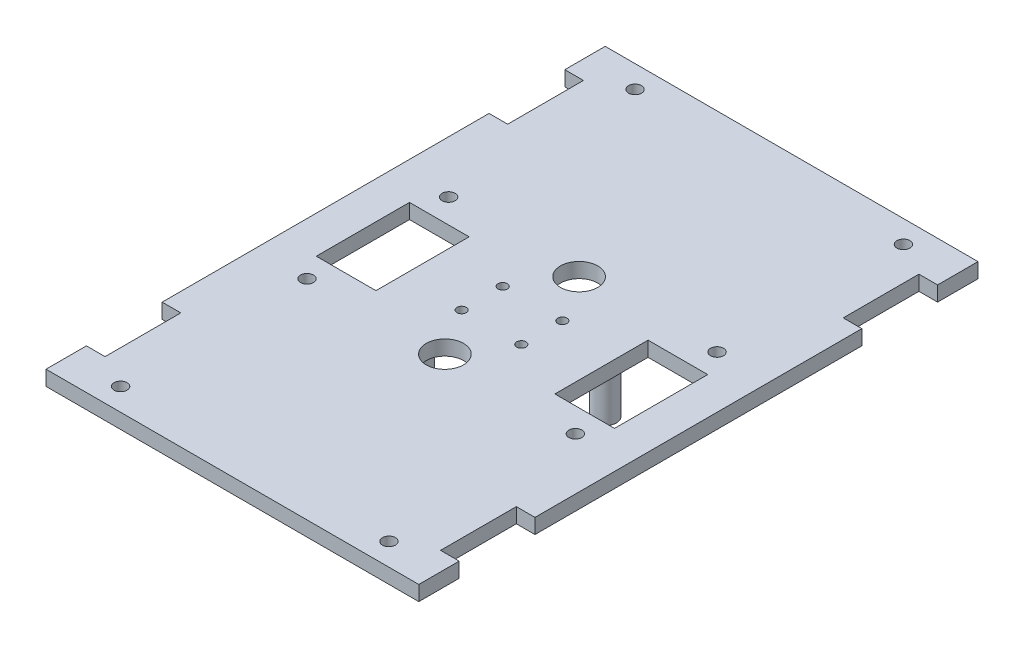
SolidWorks part; units mm, degrees
ref_plane "前视基准面" through (0, 0, 0) normal (0, 0, 1) x (1, 0, 0)
ref_plane "上视基准面" through (0, 0, 0) normal (0, 1, 0) x (1, 0, 0)
ref_plane "右视基准面" through (0, 0, 0) normal (1, 0, 0) x (0, 0, -1)
sketch "草图1" plane through (0, 0, 0) normal (0, 1, 0) x (1, 0, 0)
  line L0 (0, 0) -> (0, 8.8316) construction
  line L1 (-50, -75) -> (50, -75)
  line L2 (-50, -75) -> (-50, 75)
  line L3 (-50, 75) -> (50, 75)
  line L4 (50, -75) -> (50, 75)
  line L5 (-50, -75) -> (50, 75) construction
  line L6 (-50, 75) -> (50, -75) construction
  line L7 (0, 0) -> (12.2704, 0) construction
  point P0 (0, 0)
  dimension "D1" = 150
  dimension "D2" = 100
extrude "凸台-拉伸2" add sketch "草图1" along normal mid plane 4
sketch "草图3" plane through (0, 2, 0) normal (0, 1, 0) x (1, 0, 0)
  line L0 (-50, 75) -> (-50, -75) construction
  line L1 (-50, -75) -> (50, -75) construction
  circle A2 centre (-36, -19) radius 1.75
  circle A3 centre (-36, -69) radius 1.75
  dimension "D1" = 50
  dimension "D2" = 6
  dimension "D3" = 3.5
  dimension "D4" = 3.5
  dimension "D5" = 14
  dimension "D6" = 14
extrude "切除-拉伸1" cut sketch "草图3" against normal through all
mirror "镜向1" about plane through (0, 0, 0) normal (1, 0, 0) of "切除-拉伸1"
mirror "镜向2" about plane through (0, 0, 0) normal (0, 0, 1) of "镜向1", "切除-拉伸1"
sketch "草图5" plane through (0, -2, 0) normal (0, -1, 0) x (1, 0, 0)
  line L1 (-10, -7.5) -> (10, -7.5)
  line L2 (-10, -7.5) -> (-10, 7.5)
  line L3 (-10, 7.5) -> (10, 7.5)
  line L4 (10, -7.5) -> (10, 7.5)
  line L5 (-10, -7.5) -> (10, 7.5) construction
  line L6 (-10, 7.5) -> (10, -7.5) construction
  point P0 (0, 0)
  dimension "D1" = 15
  dimension "D2" = 20
extrude "切除-拉伸3" cut sketch "草图5" against normal blind 1
sketch "草图6" plane through (0, -1, 0) normal (0, -1, 0) x (1, 0, 0)
  line L0 (0, 0) -> (0, 10.3226) construction
  line L1 (0.2462, 0) -> (15.9669, 0) construction
  line L2 (10, 7.5) -> (-10, 7.5) construction
  line L3 (-10, 7.5) -> (-10, -7.5) construction
  circle A0 centre (-8, 5.5) radius 1.25
  circle A1 centre (8, 5.5) radius 1.25
  circle A2 centre (8, -5.5) radius 1.25
  circle A3 centre (-8, -5.5) radius 1.25
  dimension "D2" = 2.5
  dimension "D1" = 2
  dimension "D3" = 2
extrude "切除-拉伸4" cut sketch "草图6" against normal blind 3
sketch "草图8" plane through (0, 2, 0) normal (0, 1, 0) x (1, 0, 0)
  line L0 (0.8196, 0) -> (85.0823, 0) construction
  line L1 (0, 0) -> (0, -53.2019) construction
  line L2 (-50, 75) -> (-50, -75) construction
  line L3 (-40, -12.5) -> (-24, -12.5)
  line L4 (-40, -12.5) -> (-40, 12.5)
  line L5 (-40, 12.5) -> (-24, 12.5)
  line L6 (-24, -12.5) -> (-24, 12.5)
  line L7 (-40, -12.5) -> (-24, 12.5) construction
  line L8 (-40, 12.5) -> (-24, -12.5) construction
  line L9 (40, -12.5) -> (24, -12.5)
  line L10 (24, -12.5) -> (24, 12.5)
  line L11 (40, -12.5) -> (40, 12.5)
  line L12 (40, 12.5) -> (24, 12.5)
  point P4 (-32, 0)
  dimension "D1" = 10
  dimension "D2" = 16
  dimension "D3" = 25
extrude "切除-拉伸5" cut sketch "草图8" against normal through all
sketch "草图9" plane through (0, -2, 0) normal (0, -1, 0) x (1, 0, 0)
  line L0 (0, 0) -> (0, 53.2019) construction
  line L1 (0, 0) -> (78.3863, 0) construction
  line L2 (-50, 75) -> (50, 75) construction
  line L3 (-33, 63) -> (33, 63)
  line L4 (-33, 63) -> (-33, 27)
  line L5 (-33, 27) -> (33, 27)
  line L6 (33, 63) -> (33, 27)
  line L7 (-33, 63) -> (33, 27) construction
  line L8 (-33, 27) -> (33, 63) construction
  point P4 (0, 45)
  dimension "D1" = 66
  dimension "D2" = 36
  dimension "D3" = 12
extrude "切除-拉伸7" cut sketch "草图9" against normal blind 1
sketch "草图10" plane through (0, -1, 0) normal (0, -1, 0) x (1, 0, 0)
  line L0 (0, 0) -> (0, 72.7065) construction
  line L1 (-33, 45) -> (33, 45) construction
  line L2 (-33, 63) -> (-33, 27) construction
  line L3 (33, 27) -> (33, 63) construction
  circle A0 centre (-30.48, 60.55) radius 1.25
  circle A1 centre (30.48, 60.55) radius 1.25
  circle A2 centre (30.48, 29.45) radius 1.25
  circle A3 centre (-30.48, 29.45) radius 1.25
  dimension "D1" = 2.5
  dimension "D2" = 60.96
  dimension "D3" = 31.1
extrude "切除-拉伸8" cut sketch "草图10" against normal blind 2
sketch "草图11" plane through (0, -2, 0) normal (0, -1, 0) x (1, 0, 0)
  line L0 (0, 0) -> (0, -79.2258) construction
  line L1 (0, -39.6129) -> (84.8922, -39.6129) construction
  line L2 (50, -75) -> (-50, -75) construction
  line L3 (-34, -70) -> (34, -70)
  line L4 (-34, -70) -> (-34, -15)
  line L5 (-34, -15) -> (34, -15)
  line L6 (34, -70) -> (34, -15)
  line L7 (-34, -70) -> (34, -15) construction
  line L8 (-34, -15) -> (34, -70) construction
  point P5 (0, -42.5)
  dimension "D1" = 55
  dimension "D2" = 68
  dimension "D3" = 5
extrude "凸台-拉伸3" add sketch "草图11" along normal blind 3
sketch "草图12" plane through (0, -5, 0) normal (0, -1, 0) x (1, 0, 0)
  line L0 (-34, -15) -> (-34, -70) construction
  line L1 (34, -15) -> (-34, -15) construction
  line L2 (-34, -15) -> (-34, -70) construction
  circle A0 centre (-18.76, -17.54) radius 1.5
  circle A1 centre (-18.76, -65.8) radius 1.5
  circle A2 centre (32.04, -32.78) radius 1.25
  circle A3 centre (32.04, -60.72) radius 1.5
  dimension "D1" = 3
  dimension "D4" = 3
  dimension "D7" = 2.5
  dimension "D8" = 3
  dimension "D2" = 15.24
  dimension "D3" = 2.54
  dimension "D5" = 50.8
  dimension "D6" = 15.24
  dimension "D9" = 66.04
  dimension "D10" = 66.04
  dimension "D11" = 17.78
  dimension "D12" = 45.72
extrude "切除-拉伸9" cut sketch "草图12" against normal blind 3
sketch "草图13" plane through (0, -5, 0) normal (0, -1, 0) x (1, 0, 0)
  line L0 (-24, -15) -> (-24, -70)
  line L1 (-14, -15) -> (-14, -70)
  line L2 (29, -15) -> (29, -70)
  line L3 (-24, -15) -> (-34, -15)
  line L4 (34, -70) -> (34, -15)
  line L5 (34, -15) -> (-34, -15)
  line L6 (-34, -15) -> (-34, -70)
  line L7 (-34, -70) -> (34, -70)
  line L9 (29, -15) -> (-14, -15)
  line L10 (-34, -15) -> (-34, -70)
  line L11 (-34, -70) -> (-24, -70)
  line L12 (-14, -70) -> (29, -70)
  dimension "D2" = 10
  dimension "D3" = 10
  dimension "D1" = 0
extrude "切除-拉伸10" cut sketch "草图13" against normal up to surface (3 mm away) up to face at (0, -2, 45)
sketch "草图14" plane through (0, -5, 0) normal (0, -1, 0) x (1, 0, 0)
  line L0 (-14, -15) -> (-14, -70) construction
  line L1 (-24, -62.742) -> (-14, -62.742)
  line L2 (-24, -62.742) -> (-24, -20.742)
  line L3 (-24, -20.742) -> (-14, -20.742)
  line L4 (-14, -62.742) -> (-14, -20.742)
  line L5 (-24, -62.742) -> (-14, -20.742) construction
  line L6 (-24, -20.742) -> (-14, -62.742) construction
  line L7 (34, -70) -> (34, -15) construction
  line L8 (29, -15) -> (34, -15)
  line L9 (29, -15) -> (29, -27.78)
  line L10 (29, -27.78) -> (34, -27.78)
  line L11 (34, -15) -> (34, -27.78)
  line L12 (29, -70) -> (29, -15) construction
  line L13 (29, -37.78) -> (34, -37.78)
  line L14 (29, -37.78) -> (29, -57.72)
  line L15 (29, -57.72) -> (34, -57.72)
  line L16 (34, -37.78) -> (34, -57.72)
  line L17 (34, -70) -> (34, -15) construction
  line L18 (29, -15) -> (29, -70) construction
  line L19 (34, -70) -> (29, -70)
  line L20 (34, -70) -> (34, -63.72)
  line L21 (34, -63.72) -> (29, -63.72)
  line L22 (29, -70) -> (29, -63.72)
  circle A0 centre (32.04, -32.78) radius 1.25 construction
  circle A1 centre (32.04, -32.78) radius 1.25 construction
  circle A2 centre (32.04, -60.72) radius 1.5 construction
  circle A3 centre (32.04, -60.72) radius 1.5 construction
  point P0 (-19, -41.742)
  dimension "D2" = 5
  dimension "D5" = 3
  dimension "D1" = 42
  dimension "D3" = 5
  dimension "D4" = 3
extrude "切除-拉伸11" cut sketch "草图14" against normal up to surface (3 mm away)
sketch "草图15" plane through (0, -2, 0) normal (0, -1, 0) x (1, 0, 0)
  line L0 (-36, -19) -> (-36, -69) construction
  line L1 (-36, -44) -> (-12.1122, -44) construction
  line L2 (-50, -75) -> (-50, 75) construction
  line L3 (-50, -43.84) -> (-45, -43.84)
  line L4 (-50, -43.84) -> (-50, -64.16)
  line L5 (-50, -64.16) -> (-45, -64.16)
  line L6 (-45, -43.84) -> (-45, -64.16)
  line L7 (50, -75) -> (-50, -75) construction
  dimension "D1" = 20.32
  dimension "D2" = 10.84
  dimension "D3" = 5
extrude "切除-拉伸12" cut sketch "草图15" against normal through all
mirror "镜向3" about plane through (0, 0, 0) normal (0, 0, 1) of "切除-拉伸12"
mirror "镜向4" about plane through (0, 0, 0) normal (1, 0, 0) of "镜向3", "切除-拉伸12"
sketch "草图17" plane through (0, -2, 0) normal (0, -1, 0) x (1, 0, 0)
  line L0 (0, 0) -> (0, 18.3311) construction
  line L1 (0, 0) -> (14.363, 0) construction
  circle A0 centre (15, 10) radius 3
  circle A1 centre (-15, 10) radius 3
  circle A2 centre (15, -10) radius 3
  circle A3 centre (-15, -10) radius 3
  dimension "D1" = 6
  dimension "D2" = 15
  dimension "D3" = 10
extrude "凸台-拉伸4" add sketch "草图17" along normal blind 17
sketch "草图19" plane through (0, -19, 0) normal (0, -1, 0) x (1, 0, 0)
  line L0 (0, 0) -> (0, 15.8346) construction
  line L1 (0, 0) -> (18.044, 0) construction
  circle A0 centre (15, 10) radius 1.5
  circle A1 centre (-15, 10) radius 1.5
  circle A2 centre (15, -10) radius 1.5
  circle A3 centre (-15, -10) radius 1.5
  dimension "D1" = 3
extrude "切除-拉伸14" cut sketch "草图19" against normal blind 3
sketch "草图20" plane through (0, -2, 0) normal (0, -1, 0) x (1, 0, 0)
  line L0 (0, 0) -> (26.8109, 0) construction
  circle A0 centre (0, 18) radius 5
  circle A1 centre (0, -18) radius 5
  dimension "D1" = 10
  dimension "D2" = 18
extrude "切除-拉伸15" cut sketch "草图20" against normal through all
